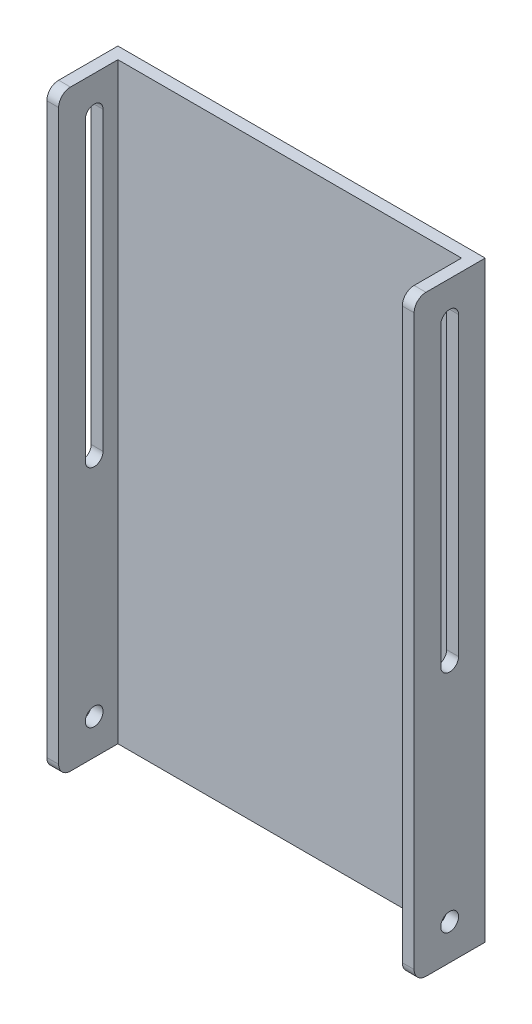
SolidWorks part; units mm, degrees
ref_plane "Front Plane" through (0, 0, 0) normal (1, 0, 0) x (0, 1, 0)
ref_plane "Top Plane" through (0, 0, 0) normal (0, 0, 1) x (0, 1, 0)
ref_plane "Right Plane" through (0, 0, 0) normal (0, 1, 0) x (-1, 0, 0)
sketch "Sketch1" plane through (0, 0, 0) normal (0, 0, 1) x (0, 1, 0)
  line L1 (-250, -150) -> (250, -150)
  line L2 (-250, -150) -> (-250, 150)
  line L3 (-250, 150) -> (250, 150)
  line L4 (250, -150) -> (250, 150)
  line L5 (-250, -150) -> (250, 150) construction
  line L6 (-250, 150) -> (250, -150) construction
  point P0 (0, 0)
  dimension "D1" = 300
  dimension "D2" = 500
extrude "Boss-Extrude1" add sketch "Sketch1" along normal blind 10
sketch "Sketch2" plane through (0, -250, 0) normal (0, -1, 0) x (1, 0, 0)
  line L0 (-150, 0) -> (-150, 60)
  line L1 (150, 0) -> (150, 60)
  dimension "D1" = 60
extrude "Extrude-Thin1" add sketch "Sketch2" against normal up to surface (500 mm away) thin up to face at (0, 250, 5) thin type mid plane wall 10
sketch "Sketch3" plane through (155, 0, 0) normal (1, 0, 0) x (0, 1, 0)
  line L0 (-220, 60) -> (-220, 0) construction
  line L1 (250, 60) -> (-250, 60) construction
  line L2 (250, 0) -> (-250, 0) construction
  line L3 (-220, 30) -> (250, 30) construction
  line L4 (250, 60) -> (250, 0) construction
  line L5 (-30, 30) -> (220, 30) construction
  line L6 (-30, 37.5) -> (220, 37.5)
  line L7 (-30, 22.5) -> (220, 22.5)
  circle A0 centre (-220, 30) radius 7.5
  arc A1 (-30, 37.5) -> (-30, 22.5) centre (-30, 30) ccw
  arc A2 (220, 22.5) -> (220, 37.5) centre (220, 30) ccw
  point P14 (95, 30)
  dimension "D2" = 15
  dimension "D3" = 7.5
  dimension "D1" = 30
  dimension "D4" = 30
  dimension "D5" = 250
extrude "Cut-Extrude1" cut sketch "Sketch3" against normal through all
fillet "Fillet1" radius 10 4 edges at (-150, 250, 60) (-150, -250, 60) (150, 250, 60) (150, -250, 60)
